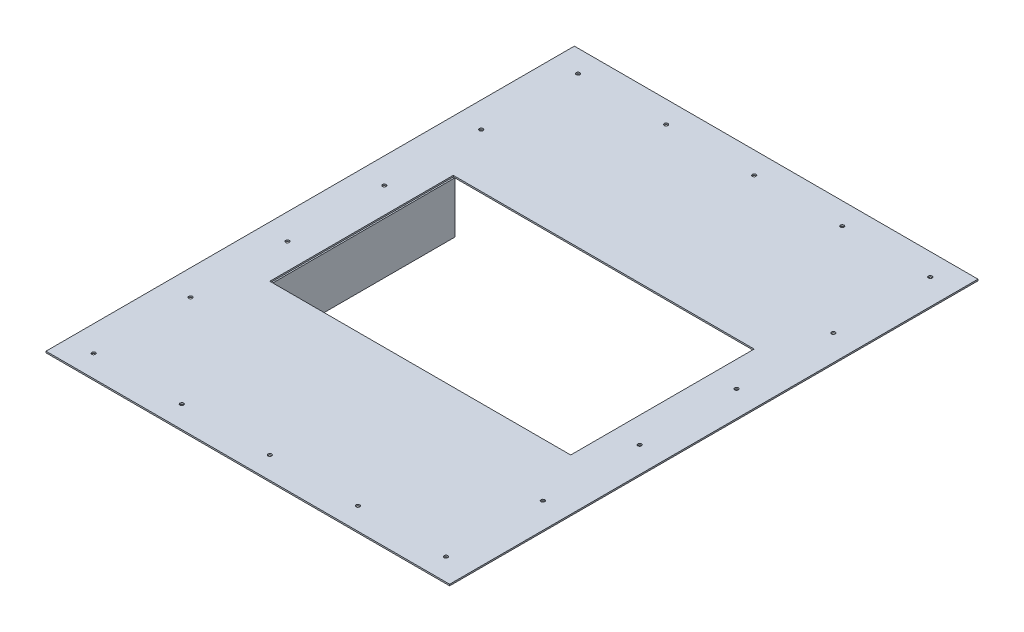
SolidWorks part; units mm, degrees
ref_plane "Ön Düzlem" through (0, 0, 0) normal (0, 0, 1) x (1, 0, 0)
ref_plane "Üst Düzlem" through (0, 0, 0) normal (0, 1, 0) x (1, 0, 0)
ref_plane "Sağ Düzlem" through (0, 0, 0) normal (1, 0, 0) x (0, 0, -1)
sketch "Sketch3" plane through (0, 0, 0) normal (0, 1, 0) x (1, 0, 0)
  line L0 (275, 0) -> (275, -546.6995) construction
  line L1 (0, 0) -> (550, 0)
  line L2 (0, 0) -> (0, -720)
  line L3 (0, -720) -> (550, -720)
  line L4 (550, 0) -> (550, -720)
  line L5 (70, -235) -> (480, -235)
  line L6 (70, -235) -> (70, -485)
  line L7 (70, -485) -> (480, -485)
  line L8 (480, -235) -> (480, -485)
  line L9 (70, -360) -> (480, -360) construction
  circle A0 centre (35, -30) radius 2.5
  circle A1 centre (35, -162) radius 2.5
  circle A2 centre (35, -294) radius 2.5
  circle A3 centre (35, -426) radius 2.5
  circle A4 centre (35, -558) radius 2.5
  circle A5 centre (35, -690) radius 2.5
  circle A6 centre (275, -30) radius 2.5
  circle A7 centre (155, -30) radius 2.5
  circle A8 centre (395, -30) radius 2.5
  circle A9 centre (155, -690) radius 2.5
  circle A10 centre (275, -690) radius 2.5
  circle A11 centre (395, -690) radius 2.5
  circle A12 centre (515, -690) radius 2.5
  circle A13 centre (515, -558) radius 2.5
  circle A14 centre (515, -426) radius 2.5
  circle A15 centre (515, -294) radius 2.5
  circle A16 centre (515, -162) radius 2.5
  circle A17 centre (515, -30) radius 2.5
  point P23 (515, -690)
  point P24 (515, -558)
  point P25 (515, -426)
  point P26 (515, -294)
  point P27 (515, -162)
  point P28 (515, -30)
  point P37 (395, -690)
  point P38 (275, -690)
  point P39 (155, -690)
  dimension "D7" = 5
  dimension "D8" = 5
  dimension "D9" = 30
  dimension "D21" = 120
  dimension "D1" = 720
  dimension "D2" = 550
  dimension "D3" = 250
  dimension "D4" = 70
  dimension "D5" = 235
  dimension "D6" = 70
  dimension "D10" = 35
  dimension "D11" = 35
  dimension "D12" = 132
  dimension "D13" = 35
  dimension "D14" = 132
  dimension "D15" = 35
  dimension "D16" = 132
  dimension "D17" = 35
  dimension "D18" = 132
  dimension "D19" = 35
  dimension "D20" = 30
  dimension "D22" = 120
extrude "Boss-Extrude2" add sketch "Sketch3" along normal blind 2
sketch "Sketch5" plane through (70, 0, 0) normal (1, 0, 0) x (0, 0, -1)
  line L1 (-485, 0) -> (-235, 0)
  line L2 (-485, 0) -> (-485, -70)
  line L3 (-485, -70) -> (-235, -70)
  line L4 (-235, 0) -> (-235, -70)
  dimension "D1" = 250
  dimension "D2" = 70
extrude "Boss-Extrude3" add sketch "Sketch5" along normal blind 2 separate body
sketch "Sketch6" plane through (480, 0, 0) normal (-1, 0, 0) x (0, 0, 1)
  line L1 (235, 0) -> (485, 0)
  line L2 (235, 0) -> (235, -70)
  line L3 (235, -70) -> (485, -70)
  line L4 (485, 0) -> (485, -70)
  dimension "D1" = 250
  dimension "D2" = 70
extrude "Boss-Extrude4" add sketch "Sketch6" along normal blind 2 separate body
